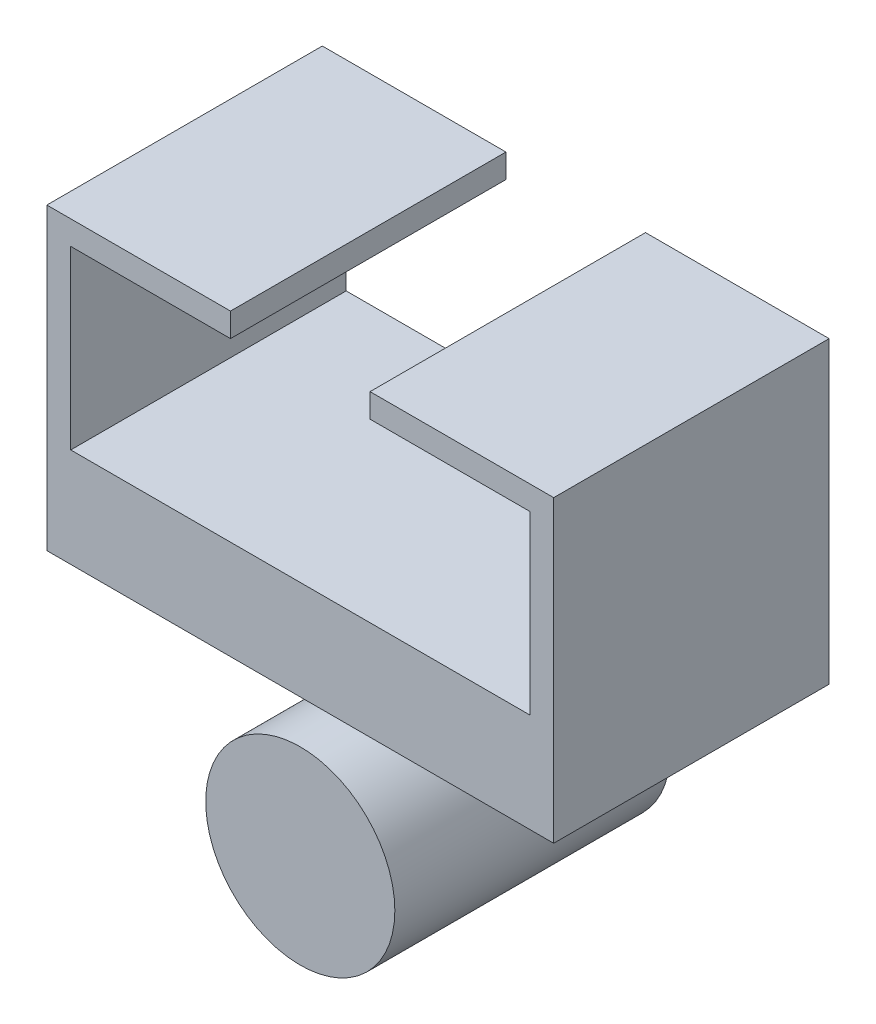
SolidWorks part; units mm, degrees
ref_plane "Front Plane" through (0, 0, 0) normal (0, 0, 1) x (1, 0, 0)
ref_plane "Top Plane" through (0, 0, 0) normal (0, 1, 0) x (1, 0, 0)
ref_plane "Right Plane" through (0, 0, 0) normal (1, 0, 0) x (0, 0, -1)
sketch "Sketch1" plane through (0, 0, 0) normal (0, 0, 1) x (1, 0, 0)
  circle A0 centre (0, 0) radius 13.081
  dimension "D1" = 26.162
extrude "Boss-Extrude1" add sketch "Sketch1" along normal blind 38.1
sketch "Sketch2" plane through (0, 0, 0) normal (0, 0, -1) x (-1, 0, 0)
  line L1 (13.081, 19.05) -> (-13.081, 19.05)
  line L2 (13.081, 19.05) -> (13.081, 0)
  line L3 (13.081, 0) -> (-13.081, 0)
  line L4 (-13.081, 19.05) -> (-13.081, 0)
  line L5 (13.081, 19.05) -> (-13.081, 0) construction
  line L6 (13.081, 0) -> (-13.081, 19.05) construction
  point P0 (0, 9.525)
  point P5 (0, 0)
  dimension "D1" = 26.162
  dimension "D2" = 19.05
extrude "Boss-Extrude2" add sketch "Sketch2" against normal blind 3.556
sketch "Sketch4" plane through (0, 19.05, 0) normal (0, 1, 0) x (1, 0, 0)
  line L1 (31.75, -38.1) -> (-31.75, -38.1)
  line L2 (31.75, -38.1) -> (31.75, 0)
  line L3 (31.75, 0) -> (-31.75, 0)
  line L4 (-31.75, -38.1) -> (-31.75, 0)
  line L5 (31.75, -38.1) -> (-31.75, 0) construction
  line L6 (31.75, 0) -> (-31.75, -38.1) construction
  point P0 (0, -19.05)
  point P5 (0, 0)
  dimension "D1" = 63.5
  dimension "D2" = 38.1
extrude "Boss-Extrude3" add sketch "Sketch4" along normal blind 13.716
sketch "Sketch6" plane through (31.75, 0, 0) normal (1, 0, 0) x (0, 0, -1)
  line L0 (0, 32.766) -> (0, 19.05) construction
  line L1 (-38.1, 19.05) -> (0, 19.05)
  line L2 (-38.1, 19.05) -> (-38.1, 57.15)
  line L3 (-38.1, 57.15) -> (0, 57.15)
  line L4 (0, 19.05) -> (0, 57.15)
  dimension "D1" = 38.1
extrude "Boss-Extrude4" add sketch "Sketch6" along normal blind 3.302
mirror "Mirror1" about plane through (0, 0, 0) normal (1, 0, 0) of "Boss-Extrude4"
sketch "Sketch7" plane through (0, 57.15, 0) normal (0, 1, 0) x (1, 0, 0)
  line L0 (-38.5572, 0) -> (38.5572, 0) construction
  line L1 (35.052, -38.1) -> (9.652, -38.1)
  line L2 (35.052, -38.1) -> (35.052, 0)
  line L3 (35.052, 0) -> (9.652, 0)
  line L4 (9.652, -38.1) -> (9.652, 0)
  dimension "D1" = 25.4
extrude "Boss-Extrude5" add sketch "Sketch7" along normal blind 3.302
mirror "Mirror2" about plane through (0, 0, 0) normal (1, 0, 0) of "Boss-Extrude5"
equation "\"F\"= 650'Strap Force"
equation "\"Sy\"= 36000'Yield Strength"
equation "\"SF\"= 4'Safety Factor"
equation "\"sigmaAllow\"= \"Sy\" / \"SF\"'Allowable Stress"
equation "\"E\"= 29000000'Young's modulus"
equation "\"deltaAllow\"= 0.005'Allowable Deflection"
equation "\"LA\"= 1.5'Feature A length"
equation "\"W\"= 2 * \"F\"'Feature A width"
equation "\"LB\"= 0.75'Feature B length"
equation "\"tB\"= \"W\" / ( \"wB\" * \"sigmaAllow\" )'Feature B thickness"
equation "\"LC\"= 1.5'Feature C length"
equation "\"wC\"= 1.125'Feature C width"
equation "\"tC\"= 0.5375'Feature C thickness"
equation "\"LD\"= 0.5'Feature D length"
equation "\"wD\"= 0.1284'Feature D width"
equation "\"LE\"= 0.5'Feature E length"
equation "\"tE\"= 0.3852'Feature E thickness"
equation "\"T_a\"= 0.498'T-beam dimension a"
equation "\"T_b\"= 0.9992'T-beam dimension b"
equation "\"T_c\"= 1.499'T-beam dimension c"
equation "\"T_width\"= \"T_a\" + 2 * \"T_b\"'T-beam width"
equation "\"DA\"= ( 16 * \"W\" * \"LA\" / ( pi * \"sigmaAllow\" ) ) ^ ( 1 / 3 )'Feature A diameter"
equation "\"wB\"= \"DA\""
